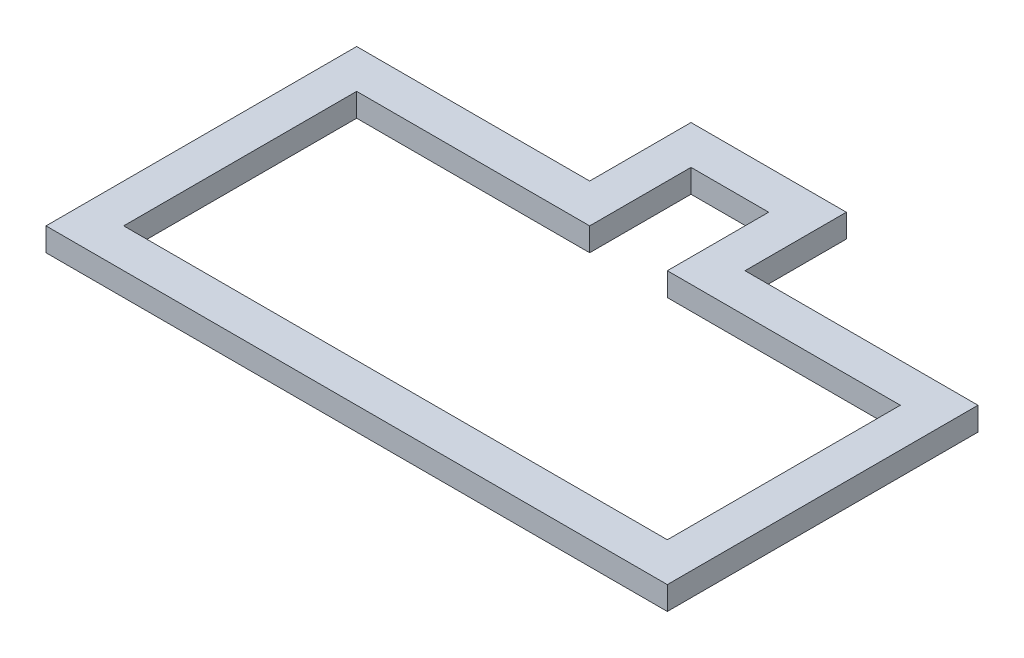
SolidWorks part; units mm, degrees
ref_plane "Front Plane" through (0, 0, 0) normal (0, 0, 1) x (1, 0, 0)
ref_plane "Top Plane" through (0, 0, 0) normal (0, 1, 0) x (1, 0, 0)
ref_plane "Right Plane" through (0, 0, 0) normal (1, 0, 0) x (0, 0, -1)
sketch "Sketch1" plane through (0, 0, 0) normal (0, 1, 0) x (1, 0, 0)
  line L1 (-399.8117, 163.4652) -> (400.1883, 163.4652)
  line L2 (-399.8117, 163.4652) -> (-399.8117, -236.5348)
  line L3 (-399.8117, -236.5348) -> (400.1883, -236.5348)
  line L4 (400.1883, 163.4652) -> (400.1883, -236.5348)
  line L5 (-349.8117, 113.4652) -> (350.1883, 113.4652)
  line L6 (-349.8117, 113.4652) -> (-349.8117, -186.5348)
  line L7 (-349.8117, -186.5348) -> (350.1883, -186.5348)
  line L8 (350.1883, 113.4652) -> (350.1883, -186.5348)
  line L17 (-49.8117, 243.9481) -> (50.1883, 243.9481)
  line L18 (-99.8117, 293.9481) -> (100.1883, 293.9481)
  line L19 (-99.8117, 293.9481) -> (-99.8117, 163.4652)
  line L20 (-99.8117, 163.4652) -> (100.1883, 163.4652)
  line L21 (100.1883, 293.9481) -> (100.1883, 163.4652)
  line L22 (-49.8117, 243.9481) -> (-49.8117, 113.4652)
  line L23 (-49.8117, 113.4652) -> (50.1883, 113.4652)
  line L24 (50.1883, 243.9481) -> (50.1883, 113.4652)
  dimension "D1" = 800
  dimension "D2" = 400
  dimension "D3" = 50
  dimension "D4" = 50
  dimension "D5" = 50
  dimension "D6" = 50
  dimension "D7" = 200
  dimension "D8" = 100
  dimension "D9" = 50
  dimension "D10" = 50
  dimension "D11" = 300
extrude "Boss-Extrude4" add sketch "Sketch1" along normal blind 30 contours L1 L24 L5 L8 L7 L6 L22 L2 L3 L4 | L17 L24 L1 L21 L18 L19 L22
equation "\"ScannerWidth\"= 800"
equation "\"ScannerLength\"= 400"
equation "\"SpineLength\"= 100"
equation "\"ScannerThickness\"= 50"
equation "\"D1@Sketch1\"=\"ScannerWidth\""
equation "\"D2@Sketch1\"=\"ScannerLength\""
equation "\"D3@Sketch1\"=\"ScannerThickness\""
equation "\"D4@Sketch1\"=\"ScannerThickness\""
equation "\"D5@Sketch1\"=\"ScannerThickness\""
equation "\"ScannerHeight\"= 30"
equation "\"SpineWidth\"= 100"
equation "\"D7@Sketch1\"=\"ScannerThickness\"*2+\"SpineWidth\""
equation "\"D6@Sketch1\"= \"ScannerThickness\""
equation "\"D9@Sketch1\"=\"ScannerThickness\""
equation "\"D8@Sketch1\"=\"SpineWidth\""
equation "\"D10@Sketch1\"=\"ScannerThickness\""
equation "\"D11@Sketch1\"=(\"ScannerWidth\"-\"SpineWidth\"-\"ScannerThickness\"*2)/2"
equation "\"D1@Boss-Extrude4\"=\"ScannerHeight\""
